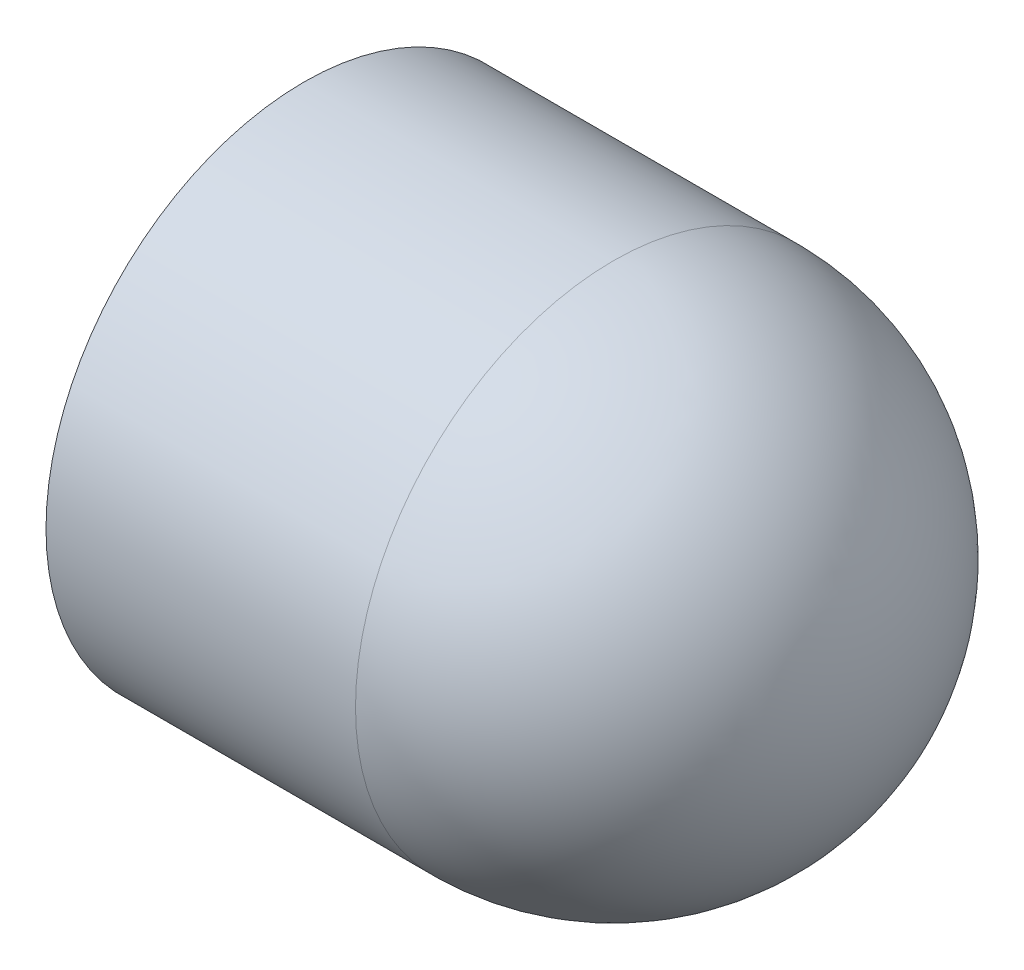
SolidWorks part; units mm, degrees
ref_plane "Front Plane" through (0, 0, 0) normal (0, 0, 1) x (1, 0, 0)
ref_plane "Top Plane" through (0, 0, 0) normal (0, 1, 0) x (1, 0, 0)
ref_plane "Right Plane" through (0, 0, 0) normal (1, 0, 0) x (0, 0, -1)
sketch "Sketch1" plane through (0, 0, 0) normal (1, 0, 0) x (0, 0, -1)
  line L0 (-16.4179, -8) -> (21.3296, -8) construction
  line L1 (-2.5, 10) -> (2.5, 10)
  line L2 (-2.5, 10) -> (-2.5, 7.5993)
  line L4 (2.5, 10) -> (2.5, 7.5993)
  arc A1 (-2.5, 7.5993) -> (2.5, 7.5993) centre (0, 0) ccw
  circle A2 centre (0, 0) radius 25
  point P5 (0, 10)
  dimension "D1" = 50
  dimension "D3" = 16
  dimension "D2" = 18
  dimension "D4" = 5
extrude "Boss-Extrude1" add sketch "Sketch1" along normal blind 15
sketch "Sketch2" plane through (15, 0, 0) normal (1, 0, 0) x (0, 0, -1)
  circle A0 centre (0, 0) radius 25
  circle A1 centre (0, 0) radius 25 construction
extrude "Boss-Extrude2" add sketch "Sketch2" along normal blind 40
fillet "Fillet1" radius 25 1 edges at (55, 0, -25)
